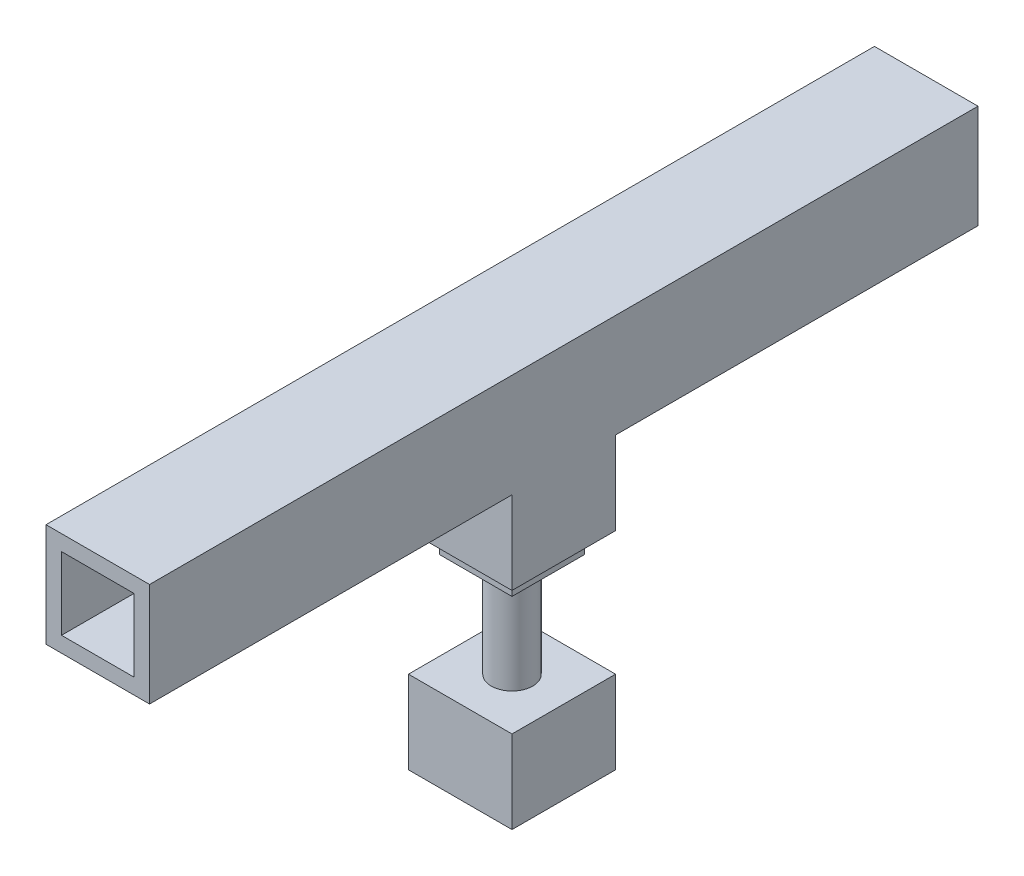
SolidWorks part; units mm, degrees
ref_plane "Спереди" through (0, 0, 0) normal (0, 0, 1) x (1, 0, 0)
ref_plane "Сверху" through (0, 0, 0) normal (0, 1, 0) x (1, 0, 0)
ref_plane "Справа" through (0, 0, 0) normal (1, 0, 0) x (0, 0, -1)
sketch "Эскиз1" plane through (0, 0, 0) normal (0, 0, 1) x (1, 0, 0)
  line L1 (-25, -25) -> (25, -25)
  line L2 (-25, -25) -> (-25, 25)
  line L3 (-25, 25) -> (25, 25)
  line L4 (25, -25) -> (25, 25)
  line L5 (-25, -25) -> (25, 25) construction
  line L6 (-25, 25) -> (25, -25) construction
  line L7 (-17.5, -17.5) -> (17.5, -17.5)
  line L8 (-17.5, -17.5) -> (-17.5, 17.5)
  line L9 (-17.5, 17.5) -> (17.5, 17.5)
  line L10 (17.5, -17.5) -> (17.5, 17.5)
  line L11 (-17.5, -17.5) -> (17.5, 17.5) construction
  line L12 (-17.5, 17.5) -> (17.5, -17.5) construction
  point P0 (0, 0)
  point P6 (0, 0)
  dimension "D1" = 50
  dimension "D2" = 35
extrude "Бобышка-Вытянуть1" add sketch "Эскиз1" along normal mid plane 400
sketch "Эскиз2" plane through (0, -25, 0) normal (0, -1, 0) x (1, 0, 0)
  line L0 (25, 200) -> (25, -200) construction
  line L1 (-25, -25) -> (25, -25)
  line L2 (-25, -25) -> (-25, 25)
  line L3 (-25, 25) -> (25, 25)
  line L4 (25, -25) -> (25, 25)
  line L5 (-25, -25) -> (25, 25) construction
  line L6 (-25, 25) -> (25, -25) construction
  line L8 (-17.5, -17.5) -> (17.5, -17.5)
  line L9 (-17.5, -17.5) -> (-17.5, 17.5)
  line L10 (-17.5, 17.5) -> (17.5, 17.5)
  line L11 (17.5, -17.5) -> (17.5, 17.5)
  line L12 (-17.5, -17.5) -> (17.5, 17.5) construction
  line L13 (-17.5, 17.5) -> (17.5, -17.5) construction
  point P0 (0, 0)
  point P9 (0, 0)
  dimension "D1" = 35
extrude "Бобышка-Вытянуть2" add sketch "Эскиз2" along normal blind 40
sketch "Эскиз3" plane through (0, -65, 0) normal (0, -1, 0) x (1, 0, 0)
  line L0 (17.5, -17.5) -> (17.5, 17.5) construction
  line L1 (-17.5, -17.5) -> (17.5, -17.5) construction
  line L2 (-17.5, 17.5) -> (-17.5, -17.5) construction
  line L3 (17.5, 17.5) -> (-17.5, 17.5) construction
  line L4 (17.5, -17.5) -> (17.5, 17.5)
  line L5 (-17.5, -17.5) -> (17.5, -17.5)
  line L6 (-17.5, 17.5) -> (-17.5, -17.5)
  line L7 (17.5, 17.5) -> (-17.5, 17.5)
extrude "Вырез-Вытянуть1" cut sketch "Эскиз3" against normal blind 60
sketch "Эскиз4" plane through (0, -65, 0) normal (0, -1, 0) x (1, 0, 0)
  line L0 (17.5, -17.5) -> (17.5, 17.5) construction
  line L1 (-17.5, -17.5) -> (17.5, -17.5) construction
  line L2 (-17.5, 17.5) -> (-17.5, -17.5) construction
  line L3 (17.5, 17.5) -> (-17.5, 17.5) construction
  line L4 (17.5, -17.5) -> (17.5, 17.5)
  line L5 (-17.5, -17.5) -> (17.5, -17.5)
  line L6 (-17.5, 17.5) -> (-17.5, -17.5)
  line L7 (17.5, 17.5) -> (-17.5, 17.5)
  circle A0 centre (0, 0) radius 10
  dimension "D1" = 20
extrude "Бобышка-Вытянуть3" add sketch "Эскиз4" along normal blind 10 separate body
sketch "Эскиз5" plane through (0, -75, 0) normal (0, -1, 0) x (1, 0, 0)
  circle A0 centre (0, 0) radius 10
  circle A1 centre (0, 0) radius 5
  dimension "D1" = 20
  dimension "D2" = 10
extrude "Бобышка-Вытянуть4" add sketch "Эскиз5" along normal blind 50 separate body
sketch "Эскиз6" plane through (0, -125, 0) normal (0, -1, 0) x (1, 0, 0)
  line L1 (-25, -25) -> (25, -25)
  line L2 (-25, -25) -> (-25, 25)
  line L3 (-25, 25) -> (25, 25)
  line L4 (25, -25) -> (25, 25)
  line L5 (-25, -25) -> (25, 25) construction
  line L6 (-25, 25) -> (25, -25) construction
  circle A0 centre (0, 0) radius 5
  point P0 (0, 0)
  dimension "D2" = 10
  dimension "D1" = 50
extrude "Бобышка-Вытянуть5" add sketch "Эскиз6" along normal blind 40
